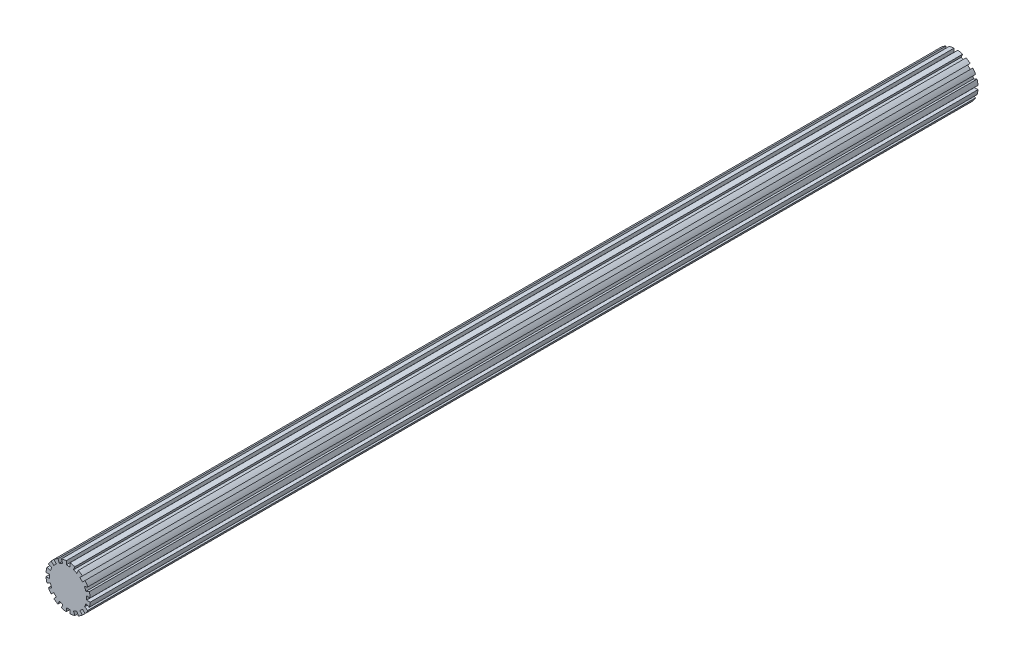
SolidWorks part; units mm, degrees
ref_plane "Front Plane" through (0, 0, 0) normal (0, 0, 1) x (1, 0, 0)
ref_plane "Top Plane" through (0, 0, 0) normal (0, 1, 0) x (1, 0, 0)
ref_plane "Right Plane" through (0, 0, 0) normal (1, 0, 0) x (0, 0, -1)
sketch "Sketch1" plane through (0, 0, 0) normal (0, 0, 1) x (1, 0, 0)
  circle A0 centre (0, 0) radius 3
extrude "Boss-Extrude1" add sketch "Sketch1" along normal blind 120
sketch "Sketch2" plane through (0, 0, 120) normal (0, 0, 1) x (1, 0, 0)
  line L0 (0, 3) -> (0, 2.5024) construction
  line L1 (-0.251, 2.5024) -> (0.251, 2.5024)
  line L2 (0.251, 2.5024) -> (0.251, 2.9895)
  line L3 (-0.251, 2.5024) -> (-0.251, 2.9895)
  line L4 (-0.251, 2.9895) -> (-0.251, 3.1233)
  line L5 (-0.251, 3.1233) -> (0.251, 3.1233)
  line L6 (0.251, 3.1233) -> (0.251, 2.9895)
  line L7 (1.4271, 2.7895) -> (1.3759, 2.6659)
  line L8 (1.1895, 2.2159) -> (1.3759, 2.6659)
  line L9 (0.7257, 2.408) -> (1.1895, 2.2159)
  line L10 (0.7257, 2.408) -> (0.9121, 2.858)
  line L11 (0.9121, 2.858) -> (0.9633, 2.9816)
  line L12 (0.9633, 2.9816) -> (1.4271, 2.7895)
  line L13 (2.386, 2.031) -> (2.2914, 1.9364)
  line L14 (1.947, 1.592) -> (2.2914, 1.9364)
  line L15 (1.592, 1.947) -> (1.947, 1.592)
  line L16 (1.592, 1.947) -> (1.9364, 2.2914)
  line L17 (1.9364, 2.2914) -> (2.031, 2.386)
  line L18 (2.031, 2.386) -> (2.386, 2.031)
  line L19 (2.9816, 0.9633) -> (2.858, 0.9121)
  line L20 (2.408, 0.7257) -> (2.858, 0.9121)
  line L21 (2.2159, 1.1895) -> (2.408, 0.7257)
  line L22 (2.2159, 1.1895) -> (2.6659, 1.3759)
  line L23 (2.6659, 1.3759) -> (2.7895, 1.4271)
  line L24 (2.7895, 1.4271) -> (2.9816, 0.9633)
  line L25 (3.1233, -0.251) -> (2.9895, -0.251)
  line L26 (2.5024, -0.251) -> (2.9895, -0.251)
  line L27 (2.5024, 0.251) -> (2.5024, -0.251)
  line L28 (2.5024, 0.251) -> (2.9895, 0.251)
  line L29 (2.9895, 0.251) -> (3.1233, 0.251)
  line L30 (3.1233, 0.251) -> (3.1233, -0.251)
  line L31 (2.7895, -1.4271) -> (2.6659, -1.3759)
  line L32 (2.2159, -1.1895) -> (2.6659, -1.3759)
  line L33 (2.408, -0.7257) -> (2.2159, -1.1895)
  line L34 (2.408, -0.7257) -> (2.858, -0.9121)
  line L35 (2.858, -0.9121) -> (2.9816, -0.9633)
  line L36 (2.9816, -0.9633) -> (2.7895, -1.4271)
  line L37 (2.031, -2.386) -> (1.9364, -2.2914)
  line L38 (1.592, -1.947) -> (1.9364, -2.2914)
  line L39 (1.947, -1.592) -> (1.592, -1.947)
  line L40 (1.947, -1.592) -> (2.2914, -1.9364)
  line L41 (2.2914, -1.9364) -> (2.386, -2.031)
  line L42 (2.386, -2.031) -> (2.031, -2.386)
  line L43 (0.9633, -2.9816) -> (0.9121, -2.858)
  line L44 (0.7257, -2.408) -> (0.9121, -2.858)
  line L45 (1.1895, -2.2159) -> (0.7257, -2.408)
  line L46 (1.1895, -2.2159) -> (1.3759, -2.6659)
  line L47 (1.3759, -2.6659) -> (1.4271, -2.7895)
  line L48 (1.4271, -2.7895) -> (0.9633, -2.9816)
  line L49 (-0.251, -3.1233) -> (-0.251, -2.9895)
  line L50 (-0.251, -2.5024) -> (-0.251, -2.9895)
  line L51 (0.251, -2.5024) -> (-0.251, -2.5024)
  line L52 (0.251, -2.5024) -> (0.251, -2.9895)
  line L53 (0.251, -2.9895) -> (0.251, -3.1233)
  line L54 (0.251, -3.1233) -> (-0.251, -3.1233)
  line L55 (-1.4271, -2.7895) -> (-1.3759, -2.6659)
  line L56 (-1.1895, -2.2159) -> (-1.3759, -2.6659)
  line L57 (-0.7257, -2.408) -> (-1.1895, -2.2159)
  line L58 (-0.7257, -2.408) -> (-0.9121, -2.858)
  line L59 (-0.9121, -2.858) -> (-0.9633, -2.9816)
  line L60 (-0.9633, -2.9816) -> (-1.4271, -2.7895)
  line L61 (-2.386, -2.031) -> (-2.2914, -1.9364)
  line L62 (-1.947, -1.592) -> (-2.2914, -1.9364)
  line L63 (-1.592, -1.947) -> (-1.947, -1.592)
  line L64 (-1.592, -1.947) -> (-1.9364, -2.2914)
  line L65 (-1.9364, -2.2914) -> (-2.031, -2.386)
  line L66 (-2.031, -2.386) -> (-2.386, -2.031)
  line L67 (-2.9816, -0.9633) -> (-2.858, -0.9121)
  line L68 (-2.408, -0.7257) -> (-2.858, -0.9121)
  line L69 (-2.2159, -1.1895) -> (-2.408, -0.7257)
  line L70 (-2.2159, -1.1895) -> (-2.6659, -1.3759)
  line L71 (-2.6659, -1.3759) -> (-2.7895, -1.4271)
  line L72 (-2.7895, -1.4271) -> (-2.9816, -0.9633)
  line L73 (-3.1233, 0.251) -> (-2.9895, 0.251)
  line L74 (-2.5024, 0.251) -> (-2.9895, 0.251)
  line L75 (-2.5024, -0.251) -> (-2.5024, 0.251)
  line L76 (-2.5024, -0.251) -> (-2.9895, -0.251)
  line L77 (-2.9895, -0.251) -> (-3.1233, -0.251)
  line L78 (-3.1233, -0.251) -> (-3.1233, 0.251)
  line L79 (-2.7895, 1.4271) -> (-2.6659, 1.3759)
  line L80 (-2.2159, 1.1895) -> (-2.6659, 1.3759)
  line L81 (-2.408, 0.7257) -> (-2.2159, 1.1895)
  line L82 (-2.408, 0.7257) -> (-2.858, 0.9121)
  line L83 (-2.858, 0.9121) -> (-2.9816, 0.9633)
  line L84 (-2.9816, 0.9633) -> (-2.7895, 1.4271)
  line L85 (-2.031, 2.386) -> (-1.9364, 2.2914)
  line L86 (-1.592, 1.947) -> (-1.9364, 2.2914)
  line L87 (-1.947, 1.592) -> (-1.592, 1.947)
  line L88 (-1.947, 1.592) -> (-2.2914, 1.9364)
  line L89 (-2.2914, 1.9364) -> (-2.386, 2.031)
  line L90 (-2.386, 2.031) -> (-2.031, 2.386)
  line L91 (-0.9633, 2.9816) -> (-0.9121, 2.858)
  line L92 (-0.7257, 2.408) -> (-0.9121, 2.858)
  line L93 (-1.1895, 2.2159) -> (-0.7257, 2.408)
  line L94 (-1.1895, 2.2159) -> (-1.3759, 2.6659)
  line L95 (-1.3759, 2.6659) -> (-1.4271, 2.7895)
  line L96 (-1.4271, 2.7895) -> (-0.9633, 2.9816)
  circle A0 centre (0, 0) radius 3
  point P8 (0, 2.5024)
  circle M14 centre (0, 0) radius 3
  dimension "D1" = 16
extrude "Cut-Extrude2" cut sketch "Sketch2" against normal through all contours L22 L21 L20 M14 | L16 L15 L14 M14 | L0 L1 L2 M14 | L0 A0 L3 L1 | L94 L93 L92 M14 | L88 L87 L86 M14 | L82 L81 L80 M14 | L76 L75 L74 M14 | L70 L69 L68 M14 | L64 L63 L62 M14 | L58 L57 L56 M14 | L52 L51 L50 M14 | L46 L45 L44 M14 | L40 L39 L38 M14 | L34 L33 L32 M14 | L28 L27 L26 M14 | L10 L9 L8 M14
